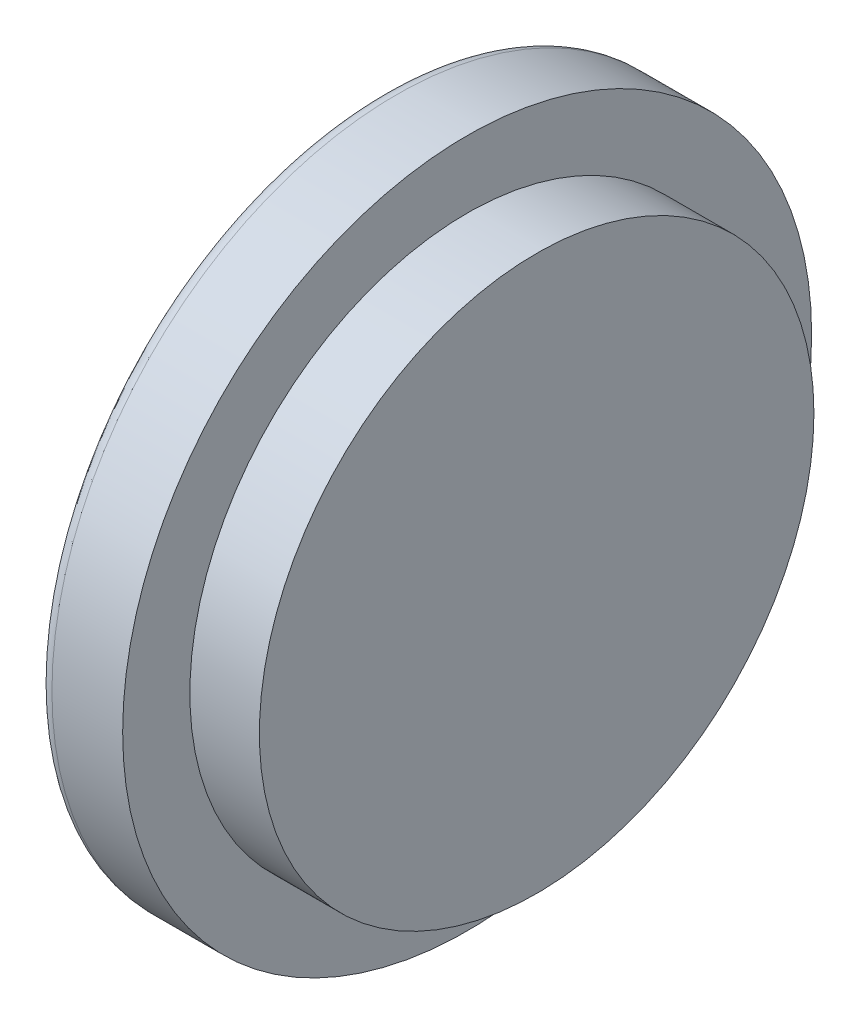
SolidWorks part; units mm, degrees
material "Mirror Cell"
ref_plane "Front Plane" through (0, 0, 0) normal (0, 0, 1) x (1, 0, 0)
ref_plane "Top Plane" through (0, 0, 0) normal (0, 1, 0) x (1, 0, 0)
ref_plane "Right Plane" through (0, 0, 0) normal (1, 0, 0) x (0, 0, -1)
sketch "Sketch1" plane through (0, 0, 0) normal (1, 0, 0) x (0, 0, -1)
  circle A0 centre (0, 0) radius 154.627
  dimension "D1" = 309.254
extrude "Boss-Extrude1" add sketch "Sketch1" along normal blind 38.1
sketch "Sketch2" plane through (38.1, 0, 0) normal (1, 0, 0) x (0, 0, -1)
  circle A1 centre (0, 0) radius 124.46
extrude "Boss-Extrude2" add sketch "Sketch2" along normal blind 69.3 from surface at -38.1 starting at face at (0, 0, -154.627)
sketch "Sketch3" plane through (0, 0, 0) normal (-1, 0, 0) x (0, 0, 1)
  circle A0 centre (0, 0) radius 139.7
extrude "Cut-Extrude1" cut sketch "Sketch3" against normal blind 6.35
fillet "Fillet1" radius 6.35 1 edges at (0, 0, -154.627)
